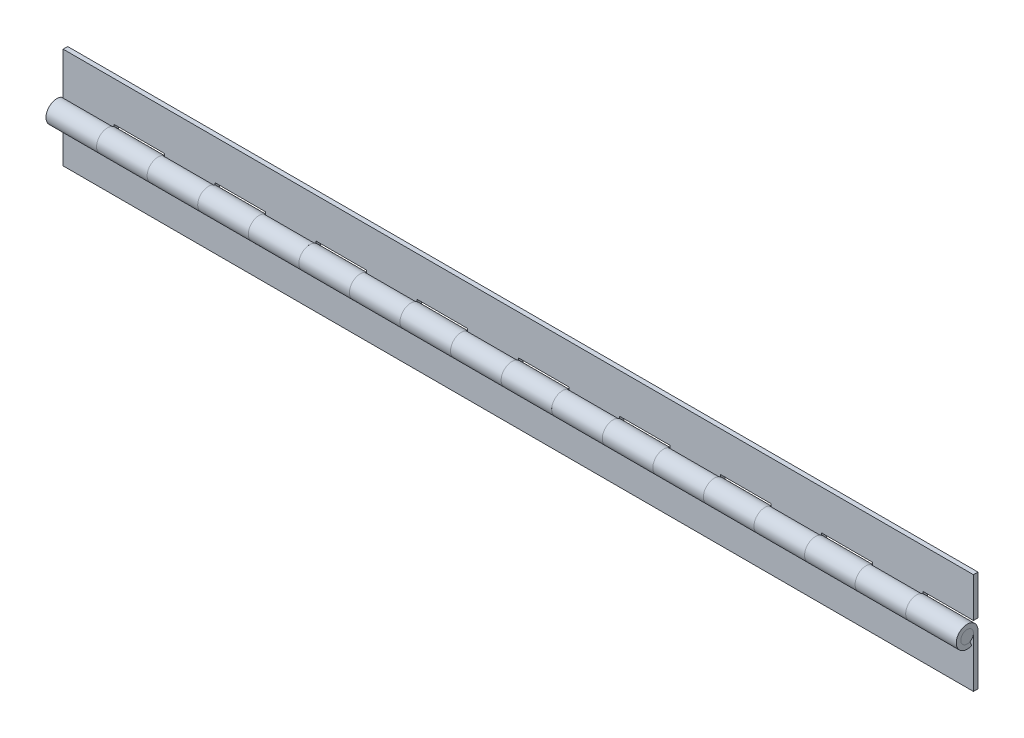
SolidWorks part; units mm, degrees
other "Bottom Leaf"
other "Top Leaf"
other "Pin" parameters "D1"=17.6771, "Angle"=25, "D2"=74.218, "Pin Diameter"=6.35, "D3"=51.2197, "Knuckle Diameter"=28.575, "Leaf Thickness"=2.286, "Overall Width"=50.8, "Length"=609.6, "Break Line"=152.4, "Knuckle Length"=25.4, "Chamfer"=0.635
ref_plane "Front Plane" through (0, 0, 0) normal (0, 0, 1) x (1, 0, 0)
ref_plane "Top Plane" through (0, 0, 0) normal (0, 1, 0) x (1, 0, 0)
ref_plane "Right Plane" through (0, 0, 0) normal (1, 0, 0) x (0, 0, -1)
sketch "Sketch1" plane through (0, 0, 0) normal (1, 0, 0) x (0, 0, -1)
  line L0 (5.461, 0) -> (5.461, -25.4) construction
  line L1 (5.461, -25.4) -> (3.175, -25.4) construction
  line L2 (3.175, -25.4) -> (3.175, -4.4432) construction
  line L3 (0, 3.175) -> (0, 5.461) construction
  line L4 (1.3418, 2.8775) -> (2.3079, 4.9493) construction
  line L5 (0, -3.175) -> (0, -5.461) construction
  line L6 (1.3418, -2.8775) -> (2.3079, -4.9493) construction
  line L7 (5.461, 0) -> (5.461, 25.4) construction
  line L8 (5.461, 25.4) -> (3.175, 25.4) construction
  line L9 (3.175, 25.4) -> (3.175, 4.4432) construction
  line L10 (0, 5.461) -> (5.461, 5.461) construction
  line L11 (0, -5.461) -> (5.461, -5.461) construction
  line L12 (3.175, -4.4432) -> (3.175, 4.4432) construction
  line L13 (3.175, 5.4864) -> (5.461, 5.4864) construction
  circle A0 centre (0, 0) radius 3.175 construction
  circle A1 centre (0, 0) radius 5.461 construction
  point P3 (0, 3.175)
  point P4 (0, -3.175)
  point P5 (-3.175, 0)
  point P6 (3.175, 0)
  point P8 (-5.461, 0)
  point P9 (0, 5.461)
  point P10 (5.461, 0)
  point P11 (0, -5.461)
  point P17 (3.175, -25.4)
  point P18 (5.461, -25.4)
  point P22 (3.175, -4.4432)
  point P24 (1.3418, 2.8775)
  point P25 (2.3079, 4.9493)
  point P30 (1.3418, -2.8775)
  point P31 (2.3079, -4.9493)
  point P34 (3.175, 4.4432)
  point P36 (3.175, 25.4)
  point P37 (5.461, 25.4)
  point P40 (5.461, -5.461)
  point P41 (5.461, 5.461)
  point P44 (3.175, 5.4864)
  point P45 (5.461, 5.4864)
  dimension "D1" = 25
  dimension "Knuckle Diameter" = 10.922
  dimension "D2" = 0.0254
sketch "Sketch2" plane through (0, 0, 0) normal (0, 0, 1) x (1, 0, 0)
  line L0 (304.8, 25.4) -> (-304.8, 25.4) construction
  line L2 (304.8, -25.4) -> (-304.8, -25.4) construction
  line L4 (-304.8, -25.4) -> (-304.8, 25.4) construction
  line L5 (304.8, -25.4) -> (304.8, 25.4) construction
  line L6 (304.8, 5.461) -> (-304.8, 5.461) construction
  line L7 (-304.8, -5.461) -> (304.8, -5.461) construction
  line L8 (304.8, 0) -> (-304.8, 0) construction
  line L9 (152.4, -25.4) -> (152.4, 25.4) construction
  line L10 (-152.4, -25.4) -> (-152.4, 25.4) construction
  line L11 (0, -25.4) -> (0, 25.4) construction
  line L12 (304.8, 4.826) -> (304.165, 5.461) construction
  point P4 (0, 25.4)
  point P9 (0, -25.4)
  point P10 (-304.8, -25.4)
  point P12 (-304.8, 25.4)
  point P13 (304.8, -25.4)
  point P14 (304.8, 25.4)
  point P18 (279.4, -5.461)
  point P19 (-304.8, -5.461)
  point P20 (-304.8, 5.461)
  point P21 (304.8, -5.461)
  point P22 (304.8, 5.461)
  point P28 (0, 0)
  point P30 (-304.8, 0)
  point P31 (304.8, 0)
  point P34 (152.4, 0)
  point P35 (152.4, -25.4)
  point P36 (152.4, 25.4)
  point P39 (-152.4, 0)
  point P40 (-152.4, 25.4)
  point P41 (-152.4, -25.4)
  point P44 (0, 0)
  point P45 (254, -5.461)
  point P49 (304.165, 5.461)
  point P50 (304.8, 4.826)
  dimension "D1" = 25.4
  dimension "D2" = 45
ref_plane "Plane1" through (304.8, 0, 0) normal (1, 0, 0) x (0, 0, -1)
sketch "Sketch3" plane through (0, 0, 0) normal (1, 0, 0) x (0, 0, -1)
  line L2 (1.3418, -2.8775) -> (2.3079, -4.9493) construction
  line L3 (1.3418, -2.8775) -> (2.3079, -4.9493)
  line L4 (3.175, -25.4) -> (3.175, -4.4432) construction
  line L5 (3.175, -25.4) -> (3.175, -4.4432)
  line L6 (5.461, 0) -> (5.461, -25.4) construction
  line L7 (5.461, 0) -> (5.461, -25.4)
  line L8 (5.461, -25.4) -> (3.175, -25.4) construction
  line L9 (5.461, -25.4) -> (3.175, -25.4)
  line L10 (3.175, 0) -> (3.175, -4.4432)
  circle A0 centre (0, 0) radius 5.461 construction
  arc A1 (5.461, 0) -> (2.3079, -4.9493) centre (0, 0) ccw
  circle A2 centre (0, 0) radius 3.175 construction
  arc A3 (3.175, 0) -> (1.3418, -2.8775) centre (0, 0) ccw
extrude "Boss-Extrude1" add sketch "Sketch3" along normal mid plane 609.6
sketch "Sketch4" plane through (0, 0, 0) normal (0, 0, 1) x (1, 0, 0)
  line L0 (279.4, -5.461) -> (279.4, 5.461)
  line L1 (304.8, 5.461) -> (-304.8, 5.461) construction
  line L2 (279.4, 5.461) -> (304.8, 5.461)
  line L3 (304.8, 5.461) -> (304.8, -5.461)
  line L4 (304.8, -5.461) -> (279.4, -5.461)
extrude "Cut-Extrude1" cut sketch "Sketch4" against normal through all both and the other way through all
pattern_linear "LPattern1" count 12 spacing 50.8 along (-1, 0, 0) of "Cut-Extrude1"
sketch "Sketch5" plane through (304.8, 0, 0) normal (1, 0, 0) x (0, 0, -1)
  line L0 (3.175, 25.4) -> (3.175, 4.4432) construction
  line L1 (5.461, 0) -> (5.461, 25.4) construction
  line L3 (3.175, 25.4) -> (3.175, 4.4432)
  line L4 (5.461, 0) -> (5.461, 25.4)
  line L6 (5.461, 25.4) -> (3.175, 25.4) construction
  line L7 (5.461, 25.4) -> (3.175, 25.4)
  line L8 (1.3418, 2.8775) -> (2.3079, 4.9493) construction
  line L9 (1.3418, 2.8775) -> (2.3079, 4.9493)
  line L10 (3.175, 4.4432) -> (3.175, 0)
  circle A0 centre (0, 0) radius 3.175 construction
  circle A1 centre (0, 0) radius 5.461 construction
  arc A2 (1.3418, 2.8775) -> (3.175, 0) centre (0, 0) ccw
  arc A3 (2.3079, 4.9493) -> (5.461, 0) centre (0, 0) ccw
extrude "Boss-Extrude2" add sketch "Sketch5" against normal blind 609.6 separate body
sketch "Sketch6" plane through (0, 0, 0) normal (0, 0, 1) x (1, 0, 0)
  line L0 (254, -5.461) -> (254, 5.461)
  line L1 (304.8, 5.461) -> (-304.8, 5.461) construction
  line L2 (254, 5.461) -> (279.4, 5.461)
  line L3 (279.4, 5.461) -> (279.4, -5.461)
  line L4 (279.4, -5.461) -> (254, -5.461)
extrude "Cut-Extrude2" cut sketch "Sketch6" against normal through all both and the other way through all
pattern_linear "LPattern2" count 12 spacing 50.8 along (-1, 0, 0) of "Cut-Extrude2"
sketch "Sketch7" plane through (304.8, 0, 0) normal (1, 0, 0) x (0, 0, -1)
  circle A0 centre (0, 0) radius 3.175 construction
  circle A1 centre (0, 0) radius 3.175
extrude "Boss-Extrude3" add sketch "Sketch7" against normal blind 609.6 separate body
chamfer "Chamfer1" distance 0.635 angle 45 2 edges at (-304.8, 0, -3.175) (304.8, 0, -3.175)
sketch "Sketch8" plane through (0, 0, 0) normal (0, 0, 1) x (1, 0, 0)
  line L0 (-304.8, 25.4) -> (304.8, 25.4) construction
  line L1 (-228.6, -25.4) -> (228.6, -25.4)
  line L2 (-228.6, -25.4) -> (-228.6, 25.4)
  line L3 (-228.6, 25.4) -> (228.6, 25.4)
  line L4 (228.6, -25.4) -> (228.6, 25.4)
  line L5 (-228.6, -25.4) -> (228.6, 25.4) construction
  line L6 (-228.6, 25.4) -> (228.6, -25.4) construction
  point P0 (0, 0)
  dimension "D1" = 457.2
extrude "Cut-Extrude3" cut sketch "Sketch8" against normal through all and the other way through all flip side to cut
sketch "Sketch9" plane through (0, 0, 0) normal (1, 0, 0) x (0, 0, -1)
  line L0 (5.461, 0) -> (5.461, 5.461) construction
  line L1 (5.461, 5.461) -> (3.175, 5.461) construction
  line L2 (3.175, 5.461) -> (3.175, 0) construction
  line L3 (1.3418, 2.8775) -> (2.3079, 4.9493) construction
  line L4 (2.3079, -4.9493) -> (1.3418, -2.8775) construction
  line L5 (3.175, 0) -> (3.175, -25.4) construction
  line L6 (3.175, -25.4) -> (5.461, -25.4) construction
  line L7 (5.461, -25.4) -> (5.461, 0) construction
  line L8 (5.461, 0) -> (5.461, 5.461)
  line L9 (5.461, 5.461) -> (3.175, 5.461)
  line L10 (3.175, 5.461) -> (3.175, 0)
  line L11 (1.3418, 2.8775) -> (2.3079, 4.9493)
  line L12 (2.3079, -4.9493) -> (1.3418, -2.8775)
  line L13 (3.175, 0) -> (3.175, -25.4)
  line L14 (3.175, -25.4) -> (5.461, -25.4)
  line L15 (5.461, -25.4) -> (5.461, 0)
  arc A0 (2.3079, 4.9493) -> (5.461, 0) centre (0, 0) ccw construction
  arc A1 (1.3418, 2.8775) -> (3.175, 0) centre (0, 0) ccw construction
  arc A2 (5.461, 0) -> (2.3079, -4.9493) centre (0, 0) ccw construction
  arc A3 (3.175, 0) -> (1.3418, -2.8775) centre (0, 0) ccw construction
  arc A4 (2.3079, 4.9493) -> (5.461, 0) centre (0, 0) ccw
  arc A5 (1.3418, 2.8775) -> (3.175, 0) centre (0, 0) ccw
  arc A6 (5.461, 0) -> (2.3079, -4.9493) centre (0, 0) ccw
  arc A7 (3.175, 0) -> (1.3418, -2.8775) centre (0, 0) ccw
extrude "Cut-Extrude4" [suppressed] cut sketch "Sketch9" against normal through all both contours A4 L13 L14 L15
sketch "Sketch10" plane through (0, 0, 0) normal (1, 0, 0) x (0, 0, -1)
  line L0 (5.461, 0) -> (5.461, 5.461) construction
  line L1 (5.461, 5.461) -> (3.175, 5.461) construction
  line L2 (3.175, 5.461) -> (3.175, 0) construction
  line L3 (1.3418, 2.8775) -> (2.3079, 4.9493) construction
  line L4 (3.175, 5.461) -> (5.461, 5.461) construction
  line L5 (5.461, 5.461) -> (5.461, 25.4) construction
  line L6 (5.461, 25.4) -> (3.175, 25.4) construction
  line L7 (3.175, 25.4) -> (3.175, 5.461) construction
  line L8 (5.461, 0) -> (5.461, 5.461)
  line L9 (5.461, 5.461) -> (3.175, 5.461)
  line L10 (3.175, 5.461) -> (3.175, 0)
  line L11 (1.3418, 2.8775) -> (2.3079, 4.9493)
  line L12 (3.175, 5.461) -> (5.461, 5.461)
  line L13 (5.461, 5.461) -> (5.461, 25.4)
  line L14 (5.461, 25.4) -> (3.175, 25.4)
  line L15 (3.175, 25.4) -> (3.175, 5.461)
  line L24 (2.3079, -4.9493) -> (1.3418, -2.8775)
  line L25 (3.175, 0) -> (3.175, -25.4)
  line L26 (3.175, -25.4) -> (5.461, -25.4)
  line L27 (5.461, -25.4) -> (5.461, 0)
  arc A0 (2.3079, 4.9493) -> (5.461, 0) centre (0, 0) ccw construction
  arc A1 (1.3418, 2.8775) -> (3.175, 0) centre (0, 0) ccw construction
  arc A2 (2.3079, 4.9493) -> (5.461, 0) centre (0, 0) ccw
  arc A3 (1.3418, 2.8775) -> (3.175, 0) centre (0, 0) ccw
  arc A8 (5.461, 0) -> (2.3079, -4.9493) centre (0, 0) ccw
  arc A9 (3.175, 0) -> (1.3418, -2.8775) centre (0, 0) ccw
extrude "Cut-Extrude5" [suppressed] cut sketch "Sketch10" against normal through all both contours A8 L8 L9 L10 | L14 L15 L9 L13
equation "\"D1@Sketch1\"=\"Angle@Sketch1\""
equation "\"D1@Sketch2\"=\"Knuckle Length@Sketch2\""
equation "\"D1@Boss-Extrude1\" = \"Length@Sketch2\""
equation "\"D1@LPattern1\" = \"Length@Sketch2\" /  ( \"Knuckle Length@Sketch2\" * 2 ) "
equation "\"D3@LPattern1\" = \"Knuckle Length@Sketch2\" * 2"
equation "\"D1@Boss-Extrude2\"=\"Length@Sketch2\""
equation "\"Chamfer@Sketch2\" = \"Pin Diameter@Sketch1\" * .1"
equation "\"D1@Boss-Extrude3\" = \"Length@Sketch2\""
equation "\"D1@Chamfer1\"=\"Chamfer@Sketch2\""
equation "\"D3@LPattern2\" = \"Knuckle Length@Sketch2\" * 2"
equation "\"D1@LPattern2\" = \"Length@Sketch2\" /  ( \"Knuckle Length@Sketch2\" * 2 ) "
